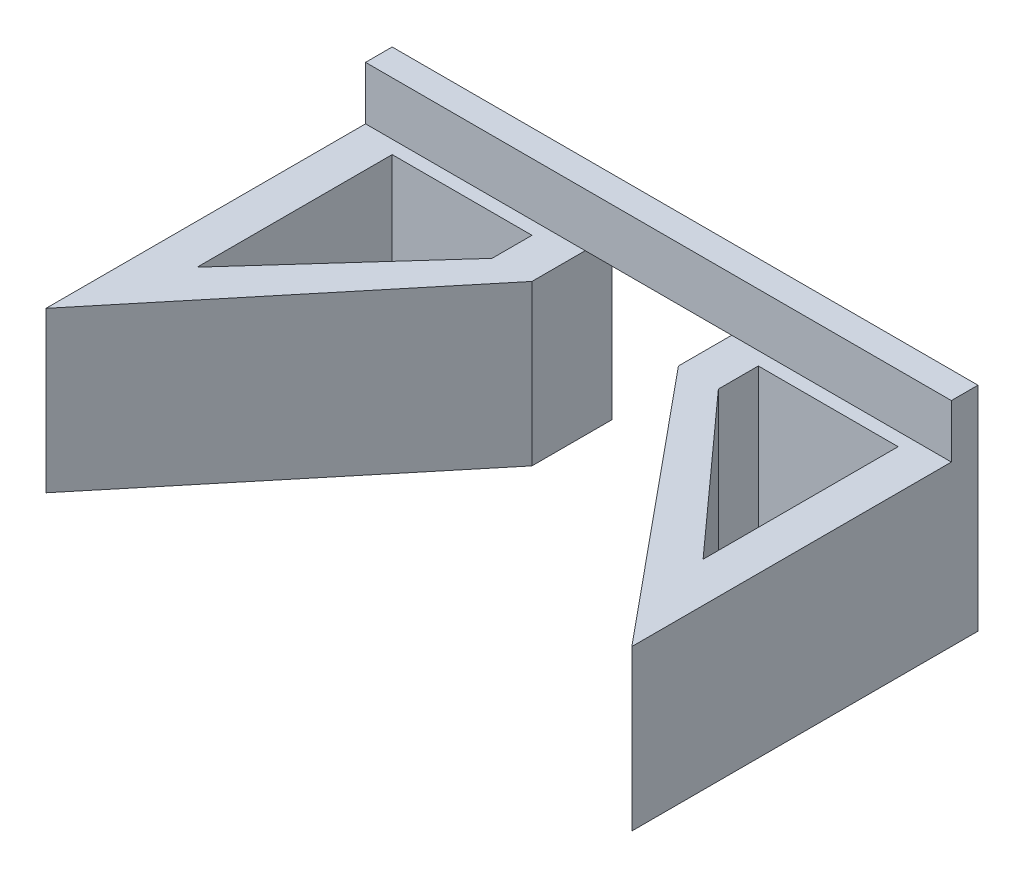
SolidWorks part; units mm, degrees
ref_plane "Front Plane" through (0, 0, 0) normal (0, 0, 1) x (1, 0, 0)
ref_plane "Top Plane" through (0, 0, 0) normal (0, 1, 0) x (1, 0, 0)
ref_plane "Right Plane" through (0, 0, 0) normal (1, 0, 0) x (0, 0, -1)
sketch "Sketch1" plane through (0, 0, 0) normal (0, 1, 0) x (1, 0, 0)
  line L0 (0, 30.1707) -> (0, -30.4719) construction
  line L1 (0, -30.4719) -> (0, 0) construction
  line L2 (0, 0) -> (-49.1968, 0) construction
  line L3 (-49.1968, 0) -> (52.6104, 0) construction
  line L4 (-110, 12.7008) -> (-110, -87.2992)
  line L5 (-110, -87.2992) -> (-27.5, 12.7008)
  line L13 (-110, 42.7008) -> (-27.5, 42.7008)
  line L14 (-27.5, 12.7008) -> (-27.5, 42.7008)
  line L20 (-110, 42.7008) -> (-110, 12.7008)
  line L26 (-95, 27.7008) -> (-95, -45.5467)
  line L27 (-95, -45.5467) -> (-42.5, 12.7008)
  line L28 (-42.5, 12.7008) -> (-42.5, 27.7008)
  line L29 (-42.5, 27.7008) -> (-95, 27.7008)
  line L30 (42.5, 12.7008) -> (42.5, 27.7008)
  line L31 (95, -45.5467) -> (42.5, 12.7008)
  line L32 (95, 27.7008) -> (95, -45.5467)
  line L33 (42.5, 27.7008) -> (95, 27.7008)
  line L34 (110, 42.7008) -> (27.5, 42.7008)
  line L35 (27.5, 12.7008) -> (27.5, 42.7008)
  line L36 (110, -87.2992) -> (27.5, 12.7008)
  line L37 (110, 12.7008) -> (110, -87.2992)
  line L38 (110, 42.7008) -> (110, 12.7008)
  dimension "D1" = 27.5
  dimension "D2" = 82.5
  dimension "D3" = 100
  dimension "D4" = 30
  dimension "D5" = 15
  dimension "D6" = 15
  dimension "D7" = 15
  dimension "D8" = 15
extrude "Boss-Extrude1" add sketch "Sketch1" along normal blind 60
sketch "Sketch3" plane through (0, 60, 0) normal (0, 1, 0) x (1, 0, 0)
  line L0 (110, -87.2992) -> (110, 42.7008) construction
  line L1 (-110, 42.7008) -> (110, 42.7008)
  line L2 (-110, 42.7008) -> (-110, 32.7008)
  line L3 (-110, 32.7008) -> (110, 32.7008)
  line L4 (110, 42.7008) -> (110, 32.7008)
  dimension "D1" = 10
extrude "Boss-Extrude3" add sketch "Sketch3" along normal blind 20
